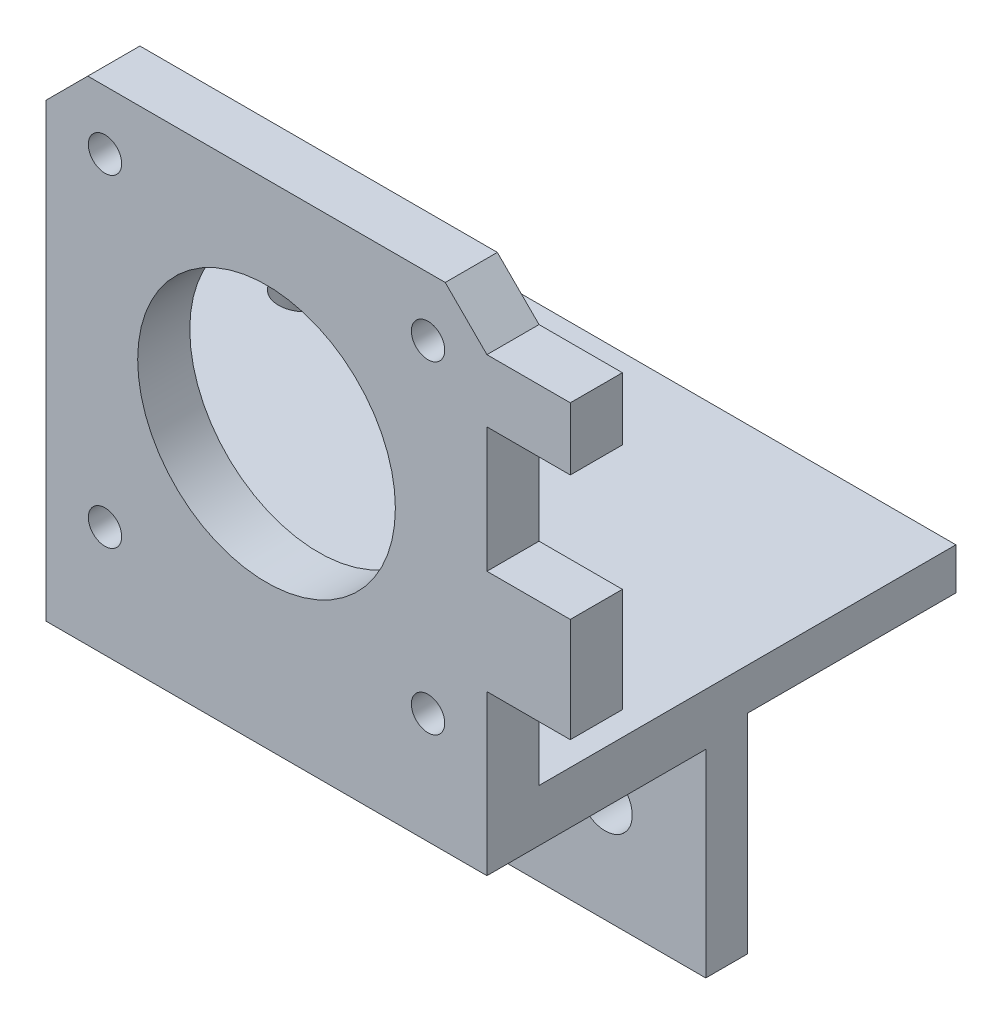
SolidWorks part; units mm, degrees
ref_plane "Přední rovina" through (0, 0, 0) normal (0, 0, 1) x (1, 0, 0)
ref_plane "Horní rovina" through (0, 0, 0) normal (0, 1, 0) x (1, 0, 0)
ref_plane "Pravá rovina" through (0, 0, 0) normal (1, 0, 0) x (0, 0, -1)
sketch "Skica1" plane through (0, 0, 0) normal (0, 0, 1) x (1, 0, 0)
  line L0 (-78.3, 11.0289) -> (-44, 11.0289) construction
  line L1 (-40, -12.9711) -> (-102.3916, -12.9711)
  line L2 (-40, -12.9711) -> (-40, 11.0289)
  line L3 (-40, 11.0289) -> (-102.3916, 11.0289)
  line L4 (-102.3916, -12.9711) -> (-102.3916, 11.0289)
extrude "Přidat vysunutím1" add sketch "Skica1" along normal blind 4
sketch "Skica2" plane through (0, 0, 4) normal (0, 0, 1) x (1, 0, 0)
  line L0 (-82.3, 49.3289) -> (-82.3, 15.0289) construction
  line L1 (-40, 11.0289) -> (-82.3, 11.0289)
  line L2 (-40, 11.0289) -> (-40, 6.0289)
  line L3 (-40, 6.0289) -> (-82.3, 6.0289)
  line L4 (-82.3, 11.0289) -> (-82.3, 6.0289)
  dimension "D1" = 5
extrude "Přidat vysunutím2" add sketch "Skica2" along normal up to surface (16 mm away)
sketch "Skica3" plane through (0, 0, 20) normal (0, 0, 1) x (1, 0, 0)
  line L0 (-82.3, 49.3289) -> (-82.3, 15.0289) construction
  line L1 (-40, 6.0289) -> (-82.3, 6.0289)
  line L2 (-40, 6.0289) -> (-40, 49.3289)
  line L3 (-44, 53.3289) -> (-78.3, 53.3289)
  line L4 (-82.3, 6.0289) -> (-82.3, 49.3289)
  line L5 (-44, 53.3289) -> (-78.3, 53.3289) construction
  line L6 (-40, 49.3289) -> (-44, 53.3289)
  line L7 (-78.3, 53.3289) -> (-82.3, 49.3289)
  circle A0 centre (-45.65, 47.6789) radius 1.6
  circle A1 centre (-76.65, 47.6789) radius 1.6
  circle A2 centre (-76.65, 16.6789) radius 1.6
  circle A3 centre (-45.65, 16.6789) radius 1.6
  circle A4 centre (-61.15, 32.1789) radius 12.3643
  dimension "D1" = 3.2
  dimension "D2" = 2
  dimension "D3" = 2
extrude "Přidat vysunutím5" add sketch "Skica3" along normal blind 5
chamfer "Zkosení1" distance 16 angle 45 1 edges at (-82.3, 8.5289, 4)
sketch "Skica4" plane through (0, 0, 4) normal (0, 0, 1) x (1, 0, 0)
  line L0 (-89.6556, -12.9711) -> (-89.6556, -2.9711) construction
  line L1 (-102.3916, -12.9711) -> (-40, -12.9711) construction
  circle A0 centre (-89.6556, -2.9711) radius 2.6
  circle A1 centre (-69.6556, -2.9711) radius 2.6
  circle A2 centre (-49.6556, -2.9711) radius 2.6
  dimension "D2" = 5.2
  dimension "D1" = 10
  dimension "D3" = 3
extrude "Odebrat vysunutím1" cut sketch "Skica4" against normal blind 4
sketch "Skica5" plane through (0, 0, 0) normal (0, 0, -1) x (-1, 0, 0)
  line L0 (350, 7.0289) -> (0, 7.0289) construction
  line L1 (40, 11.0289) -> (102.3916, 11.0289)
  line L2 (40, 11.0289) -> (40, 7.0289)
  line L3 (40, 7.0289) -> (102.3916, 7.0289)
  line L4 (102.3916, 11.0289) -> (102.3916, 7.0289)
  line L6 (102.3916, 11.0289) -> (102.3916, -12.9711) construction
extrude "Přidat vysunutím6" add sketch "Skica5" along normal up to surface (20 mm away)
sketch "Skica6" plane through (0, 11.0289, 0) normal (0, 1, 0) x (1, 0, 0)
  line L0 (-40, 20) -> (-102.3916, 20) construction
  line L1 (-102.3916, -4) -> (-102.3916, 20) construction
  circle A0 centre (-92.3916, 10) radius 2.6
  dimension "D2" = 5.2
  dimension "D1" = 10
  dimension "D3" = 10
extrude "Odebrat vysunutím2" cut sketch "Skica6" against normal blind 4
sketch "Skica7" plane through (-40, 0, 0) normal (1, 0, 0) x (0, 0, -1)
  line L0 (-20, 11.0289) -> (-20, 49.3289) construction
  line L1 (-25, 49.3289) -> (-20, 49.3289)
  line L2 (-25, 49.3289) -> (-25, 43.3289)
  line L3 (-25, 43.3289) -> (-20, 43.3289)
  line L4 (-20, 49.3289) -> (-20, 43.3289)
  line L5 (-25, 6.0289) -> (-25, 49.3289) construction
  line L6 (-25, 31.3289) -> (-20, 31.3289)
  line L7 (-25, 31.3289) -> (-25, 21.3289)
  line L8 (-25, 21.3289) -> (-20, 21.3289)
  line L9 (-20, 31.3289) -> (-20, 21.3289)
  line L10 (20, 31.3289) -> (-360, 31.3289) construction
  line L11 (20, 43.3289) -> (-360, 43.3289) construction
  dimension "D1" = 10
extrude "Přidat vysunutím7" add sketch "Skica7" along normal blind 8
